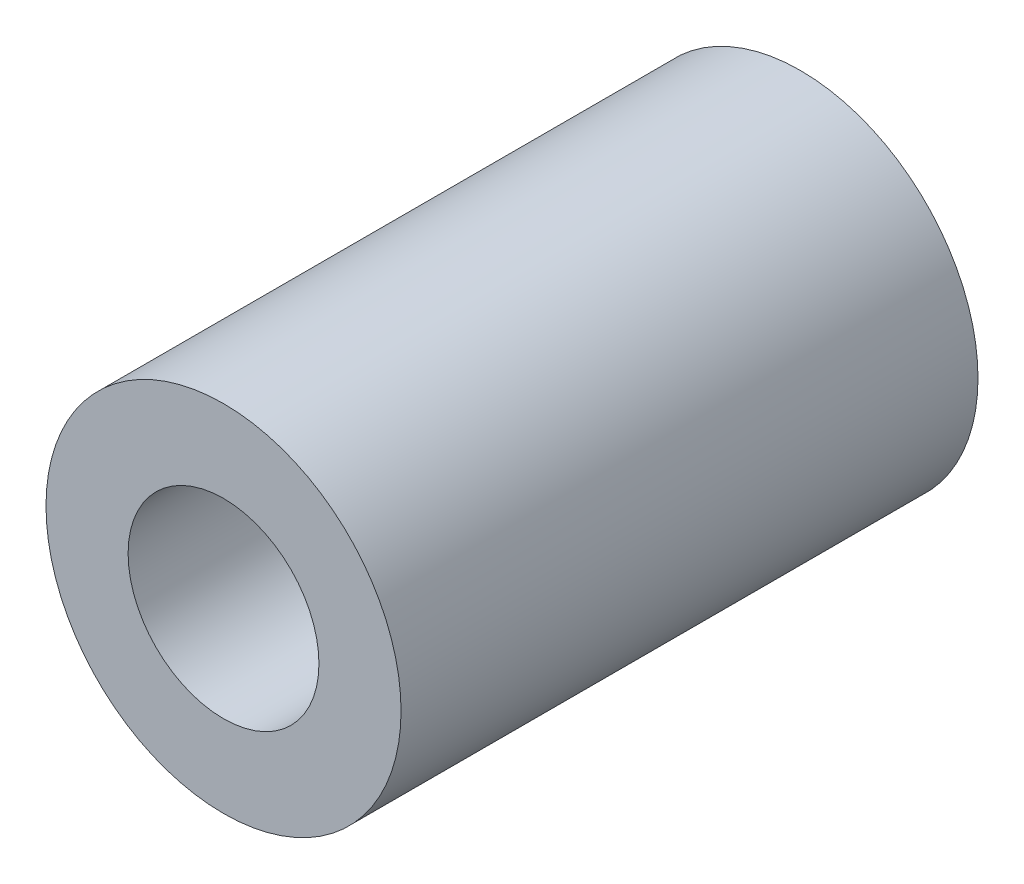
SolidWorks part; units mm, degrees
ref_plane "Front Plane" through (0, 0, 0) normal (0, 0, 1) x (1, 0, 0)
ref_plane "Top Plane" through (0, 0, 0) normal (0, 1, 0) x (1, 0, 0)
ref_plane "Right Plane" through (0, 0, 0) normal (1, 0, 0) x (0, 0, -1)
sketch "Spacer_between_POM_mounting_ears_profile" plane through (0, 0, 0) normal (0, 0, 1) x (1, 0, 0)
  circle A0 centre (0, 0) radius 4
  circle A1 centre (0, 0) radius 2.15
  dimension "D1" = 8
  dimension "D2" = 4.3
extrude "Spacer_between_POM_mounting_ears" add sketch "Spacer_between_POM_mounting_ears_profile" along normal blind 13
